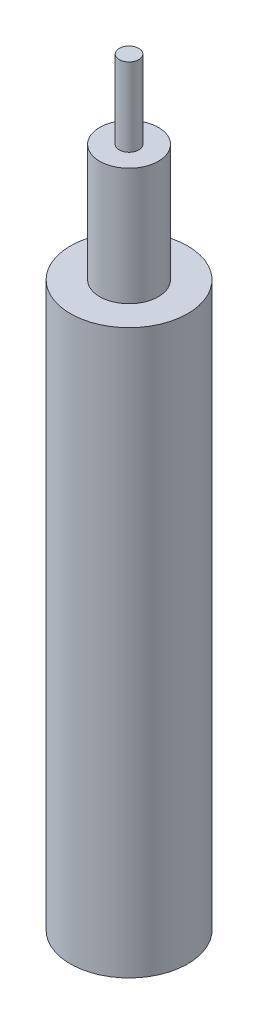
SolidWorks part; units mm, degrees
ref_plane "Front Plane" through (0, 0, 0) normal (0, 0, 1) x (1, 0, 0)
ref_plane "Top Plane" through (0, 0, 0) normal (0, 1, 0) x (1, 0, 0)
ref_plane "Right Plane" through (0, 0, 0) normal (1, 0, 0) x (0, 0, -1)
sketch "Sketch1" plane through (0, 0, 0) normal (0, 1, 0) x (1, 0, 0)
  circle A0 centre (0, 0) radius 2.3813
  dimension "D1" = 4.7625
extrude "Boss-Extrude1" add sketch "Sketch1" against normal blind 9.525
sketch "Sketch2" plane through (0, -9.525, 0) normal (0, -1, 0) x (-1, 0, 0)
  circle A0 centre (0, 0) radius 4.7625
  dimension "D1" = 9.525
extrude "Boss-Extrude2" add sketch "Sketch2" along normal blind 45.72
sketch "Sketch3" plane through (0, 0, 0) normal (0, 1, 0) x (1, 0, 0)
  circle A0 centre (0, 0) radius 0.7937
extrude "Boss-Extrude3" add sketch "Sketch3" along normal blind 6.35
